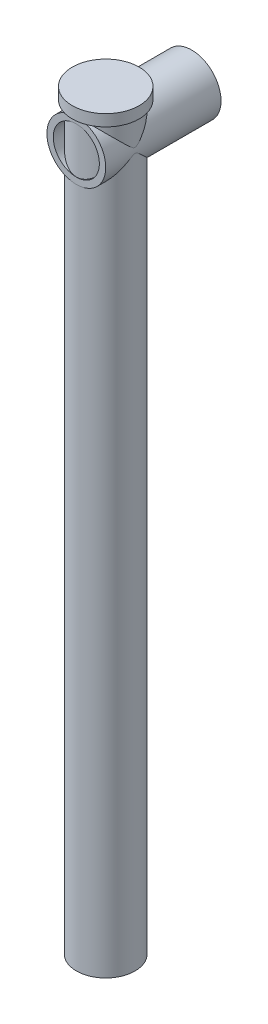
SolidWorks part; units mm, degrees
ref_plane "Alzado" through (0, 0, 0) normal (0, 0, 1) x (1, 0, 0)
ref_plane "Planta" through (0, 0, 0) normal (0, 1, 0) x (1, 0, 0)
ref_plane "Vista lateral" through (0, 0, 0) normal (1, 0, 0) x (0, 0, -1)
sketch "Croquis1" plane through (0, 0, 0) normal (0, 0, 1) x (1, 0, 0)
  circle A0 centre (0, 0) radius 12.75
  circle A1 centre (0, 0) radius 10
extrude "Saliente-Extruir1" add sketch "Croquis1" along normal blind 50
ref_plane "Plano1" through (0, -12.7, 0) normal (0, 1, 0) x (1, 0, 0)
sketch "Croquis2" plane through (0, -12.7, 0) normal (0, 1, 0) x (1, 0, 0)
  circle A0 centre (0, -37.25) radius 12.7
extrude "Saliente-Extruir2" add sketch "Croquis2" against normal blind 295.45 and the other way blind 25.4
sketch "Croquis3" plane through (0, -12.7, 0) normal (0, 1, 0) x (1, 0, 0)
  circle A0 centre (0, -37.25) radius 10
extrude "Cortar-Extruir1" cut sketch "Croquis3" along normal through all both and the other way through all
sketch "Croquis4" plane through (0, 0, 0) normal (0, 0, 1) x (1, 0, 0)
  circle A0 centre (0, 0) radius 10
extrude "Cortar-Extruir2" cut sketch "Croquis4" along normal blind 42
ref_plane "Plano2" through (0, 12.7, 0) normal (0, 1, 0) x (1, 0, 0)
sketch "Croquis5" plane through (0, 12.7, 0) normal (0, 1, 0) x (1, 0, 0)
  circle A0 centre (0, -37.25) radius 14.5
extrude "Saliente-Extruir4" add sketch "Croquis5" along normal blind 5 separate body
